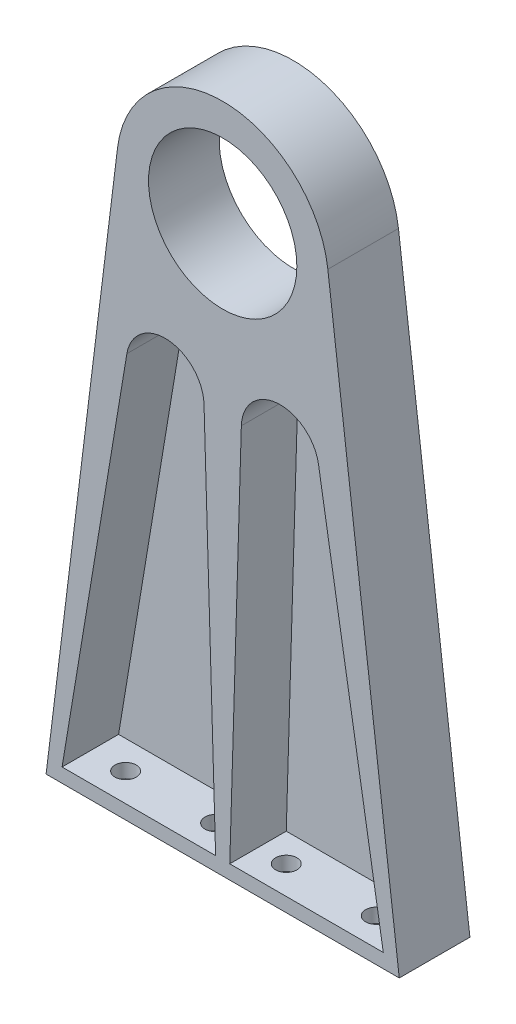
SolidWorks part; units mm, degrees
ref_plane "前视基准面" through (0, 0, 0) normal (0, 0, 1) x (1, 0, 0)
ref_plane "上视基准面" through (0, 0, 0) normal (0, 1, 0) x (1, 0, 0)
ref_plane "右视基准面" through (0, 0, 0) normal (1, 0, 0) x (0, 0, -1)
sketch "草图1" plane through (0, 0, 0) normal (0, 0, 1) x (1, 0, 0)
  line L0 (-25, 0) -> (25, 0)
  line L1 (-25, 0) -> (-14.8868, 81.8396)
  line L2 (25, 0) -> (14.8868, 81.8396)
  circle A0 centre (0, 80) radius 10.5
  arc A1 (14.8868, 81.8396) -> (-14.8868, 81.8396) centre (0, 80) ccw
  point P4 (0, 0)
  dimension "D2" = 21
  dimension "D3" = 30
  dimension "D1" = 50
  dimension "D4" = 80
extrude "凸台-拉伸1" add sketch "草图1" along normal blind 10
sketch "草图2" plane through (0, 0, 10) normal (0, 0, 1) x (1, 0, 0)
  line L0 (-13.565, 57.2626) -> (-22.7376, 2)
  line L1 (-2.6417, 56.5276) -> (-1, 2)
  line L2 (2.6417, 56.5276) -> (1, 2)
  line L3 (13.565, 57.2626) -> (22.7376, 2)
  line L4 (1, 2) -> (22.7376, 2)
  line L11 (-6.3486, 61.5624) -> (-8.1392, 56.362) construction
  line L13 (22.7376, 2) -> (12.9019, 81.5943)
  line L14 (-22.7376, 2) -> (22.7376, 2)
  line L15 (-12.9019, 81.5943) -> (-22.7376, 2)
  line L17 (-22.7376, 2) -> (-1, 2)
  line L24 (6.3486, 61.5624) -> (8.1392, 56.362) construction
  arc A7 (-15.5208, 60.4014) -> (13.111, 58.7138) centre (0, 80) ccw construction
  arc A10 (-2.6417, 56.5276) -> (-13.565, 57.2626) centre (-8.1392, 56.362) ccw
  arc A11 (13.565, 57.2626) -> (2.6417, 56.5276) centre (8.1392, 56.362) ccw
  point P0 (0, 38.9049)
  dimension "D6" = 50
  dimension "D7" = 11
  dimension "D8" = 11
  dimension "D2" = 2
extrude "切除-拉伸2" cut sketch "草图2" against normal blind 8
sketch "草图3" plane through (0, 2, 0) normal (0, 1, 0) x (1, 0, 0)
  line L0 (-1, -2) -> (-1, -10) construction
  line L2 (-22.7376, -2) -> (-1, -2) construction
  line L4 (1, -2) -> (22.7376, -2) construction
  line L5 (1, -2) -> (1, -10) construction
  circle A0 centre (-17.74, -6) radius 1.5
  circle A1 centre (-5, -6) radius 1.5
  circle A2 centre (5, -6) radius 1.5
  circle A3 centre (17.74, -6) radius 1.5
  dimension "D1" = 4
  dimension "D2" = 12.74
  dimension "D5" = 3
  dimension "D6" = 3
  dimension "D11" = 3
  dimension "D12" = 3
  dimension "D3" = 4
  dimension "D4" = 4
  dimension "D7" = 12.74
  dimension "D8" = 4
  dimension "D9" = 4
  dimension "D10" = 4
extrude "切除-拉伸3" cut sketch "草图3" against normal through all
